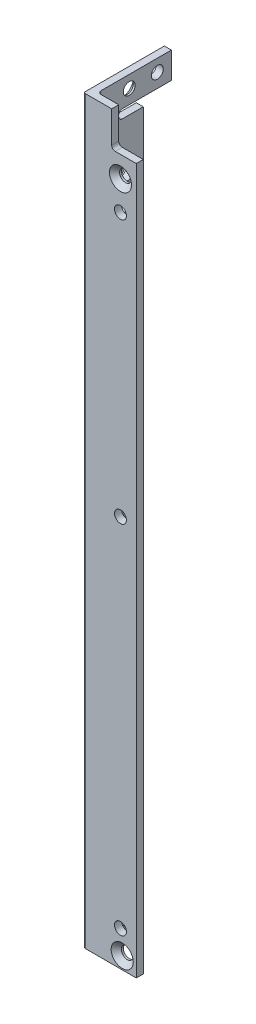
SolidWorks part; units mm, degrees
material "6061-T6 (SS)"
ref_plane "Front Plane" through (0, 0, 0) normal (0, 0, 1) x (1, 0, 0)
ref_plane "Top Plane" through (0, 0, 0) normal (0, 1, 0) x (1, 0, 0)
ref_plane "Right Plane" through (0, 0, 0) normal (1, 0, 0) x (0, 0, -1)
sketch "Sketch1" plane through (0, 0, 0) normal (0, 1, 0) x (1, 0, 0)
  line L1 (0, 0) -> (15, 0)
  line L2 (0, 0) -> (0, 15)
  line L3 (0, 15) -> (15, 15)
  line L4 (15, 0) -> (15, 15)
  line L5 (15, 15) -> (2, 15)
  line L6 (15, 15) -> (15, 2)
  line L7 (15, 2) -> (2, 2)
  line L8 (2, 15) -> (2, 2)
  dimension "D1" = 15
  dimension "D2" = 15
  dimension "D3" = 2
  dimension "D4" = 2
extrude "Boss-Extrude1" add sketch "Sketch1" along normal blind 211 contours L8 L3 L2 L1 L4 L7
sketch "Sketch2" plane through (0, 0, 0) normal (1, 0, 0) x (0, 0, -1)
  line L0 (114.6002, 211) -> (212.4893, 211)
  line L1 (35, 211) -> (50, 211)
  line L2 (0, 211) -> (15, 211) construction
  circle A0 centre (56.7892, 32.4507) radius 1.6
  circle A1 centre (56.7892, 79.8607) radius 1.55
  circle A2 centre (56.7892, 103.4607) radius 1.55
  circle A3 centre (56.7892, 125.1207) radius 1.6
  circle A4 centre (56.7892, 137.8117) radius 1.55
  circle A5 centre (56.7892, 150.8117) radius 1.55
  circle A6 centre (56.7892, 178.5483) radius 1.55
  circle A7 centre (-39.5, 32.4507) radius 1.6
  circle A8 centre (-39.5, 79.8607) radius 1.6
  circle A9 centre (-39.5, 103.4607) radius 1.6
  circle A10 centre (-39.5, 125.1207) radius 1.6
  circle A11 centre (-39.5, 137.8117) radius 1.6
  circle A12 centre (-39.5, 150.8117) radius 1.6
  circle A13 centre (-39.5, 178.5483) radius 1.6
  dimension "D1" = 27.7366
  dimension "D2" = 13
  dimension "D3" = 12.691
  dimension "D4" = 21.66
  dimension "D5" = 23.6
  dimension "D6" = 47.41
  dimension "D7" = 32.4517
sketch "Sketch3" plane through (0, 0, 0) normal (-1, 0, 0) x (0, 0, 1)
  line L0 (-10.5, 211) -> (-10.5, 0)
  line L1 (39.5, 137.8117) -> (-10.5, 137.8117)
  line L3 (39.5, 178.5483) -> (-10.5, 178.5483)
  line L4 (-10.5, 178.5483) -> (39.5, 150.8117)
  line L5 (39.5, 150.8117) -> (-10.5, 150.8117)
  line L6 (-10.5, 150.8117) -> (39.5, 137.8117)
  line L7 (39.5, 125.1207) -> (-10.5, 125.1207)
  line L8 (-10.5, 125.1207) -> (39.5, 103.4607)
  line L9 (39.5, 103.4607) -> (-10.5, 103.4607)
  line L10 (-10.5, 103.4607) -> (39.5, 79.8607)
  line L11 (39.5, 79.8607) -> (-10.5, 79.8607)
  line L12 (-10.5, 79.8607) -> (39.5, 32.4507)
  line L13 (39.5, 32.4507) -> (-10.5, 32.4507)
  line L14 (-15, 211) -> (-15, 0) construction
  dimension "D1" = 4.5
hole_wizard "CSK for M3 Flat Head Machine Screw1" positions "Sketch4" profile "Sketch5" countersink size "M3" standard "ANSI Metric" end condition through all
sketch "Sketch4" plane through (0, 0, 0) normal (-1, 0, 0) x (0, 0, 1)
  line L0 (-6, 87.589) -> (-15, 87.589) construction
  point P0 (-10.5, 178.5483)
  point P3 (-10.5, 150.8117)
  point P6 (-10.5, 125.1207)
  point P9 (-10.5, 91.719)
  point P12 (-10.5, 32.4507)
  point P15 (-10.5, 79.8607)
  point P18 (-10.5, 137.8117)
  dimension "D1" = 4.13
sketch "Sketch5" plane through (0, 178.5483, -10.5) normal (0, 1, 0) x (0, 0, 1)
  line L0 (0, 0) -> (0, 15)
  line L1 (0, 15) -> (1.7, 15)
  line L2 (1.7, 15) -> (1.7, 1.45)
  line L3 (1.7, 1.45) -> (3.15, 0)
  line L5 (3.15, 0) -> (0, 0)
  line L6 (-1.7, 1.45) -> (-3.15, 0) construction
  line L11 (0, -6.35) -> (0, 107.95) construction
  dimension "Thru Hole Dia." = 3.4
  dimension "Thru Hole Depth" = 15
  dimension "Near C'Sink Dia." = 6.3
  dimension "Near C'Sink Angle" = 90
sketch "Sketch6" plane through (0, 0, 0) normal (0, 0, 1) x (1, 0, 0)
  line L0 (15, 211) -> (15, 0) construction
  line L1 (15, 211) -> (8, 211)
  line L2 (15, 211) -> (15, 201)
  line L3 (15, 201) -> (8, 201)
  line L4 (8, 211) -> (8, 201)
  line L5 (0, 211) -> (15, 211) construction
  line L6 (0, 211) -> (0, 0) construction
  dimension "D1" = 0
  dimension "D2" = 8
  dimension "D3" = 10
extrude "Cut-Extrude1" cut sketch "Sketch6" against normal through all
sketch "Sketch7" plane through (0, 0, 0) normal (-1, 0, 0) x (0, 0, 1)
  line L0 (-15, 211) -> (-15, 0) construction
  line L1 (-15, 201) -> (-8, 201)
  line L2 (-15, 201) -> (-15, 203.5)
  line L3 (-15, 203.5) -> (-8, 203.5)
  line L4 (-8, 201) -> (-8, 203.5)
  line L5 (0, 211) -> (0, 0) construction
  dimension "D1" = 8
  dimension "D2" = 2.5
extrude "Cut-Extrude2" cut sketch "Sketch7" against normal through all
sketch "Sketch8" plane through (0, 0, 0) normal (-1, 0, 0) x (0, 0, 1)
  line L0 (0, 211) -> (-15, 211) construction
  line L2 (-15, 211) -> (-15, 203.5) construction
  circle A0 centre (-11, 207.5) radius 1.0458
  dimension "D1" = 3.5
  dimension "D2" = 4
hole_wizard "CSK for M3 Flat Head Machine Screw2" positions "Sketch9" profile "Sketch10" countersink size "M3" standard "ANSI Metric" end condition through all
sketch "Sketch9" plane through (0, 0, 0) normal (-1, 0, 0) x (0, 0, 1)
  point P0 (-11, 207.5)
sketch "Sketch10" plane through (0, 207.5, -11) normal (0, 1, 0) x (0, 0, 1)
  line L0 (0, 0) -> (0, 15)
  line L1 (0, 15) -> (1.7, 15)
  line L2 (1.7, 15) -> (1.7, 1.45)
  line L3 (1.7, 1.45) -> (3.15, 0)
  line L5 (3.15, 0) -> (0, 0)
  line L6 (-1.7, 1.45) -> (-3.15, 0) construction
  line L11 (0, -6.35) -> (0, 107.95) construction
  dimension "Thru Hole Dia." = 3.4
  dimension "Thru Hole Depth" = 15
  dimension "Near C'Sink Dia." = 6.3
  dimension "Near C'Sink Angle" = 90
sketch "Sketch11" plane through (0, 0, 0) normal (0, 0, 1) x (1, 0, 0)
  line L0 (15, 201) -> (15, 0) construction
  line L1 (0, 0) -> (15, 0) construction
  circle A0 centre (11, 3.5) radius 2.9907
  dimension "D1" = 4
  dimension "D2" = 3.5
hole_wizard "CSK for M3 Flat Head Machine Screw3" positions "Sketch14" profile "Sketch15" countersink size "M3" standard "ANSI Metric" end condition through all
sketch "Sketch14" plane through (0, 0, 0) normal (0, 0, 1) x (1, 0, 0)
  line L0 (15, 201) -> (15, 0) construction
  line L1 (0, 211) -> (8, 211) construction
  circle A0 centre (10.5, 195) radius 2.222
  point P0 (11, 3.5)
  point P3 (10.5, 195)
  dimension "D1" = 4.5
  dimension "D2" = 16
sketch "Sketch15" plane through (11, 3.5, 0) normal (1, 0, 0) x (0, -1, 0)
  line L0 (0, 0) -> (0, 15)
  line L1 (0, 15) -> (1.7, 15)
  line L2 (1.7, 15) -> (1.7, 1.45)
  line L3 (1.7, 1.45) -> (3.15, 0)
  line L5 (3.15, 0) -> (0, 0)
  line L6 (-1.7, 1.45) -> (-3.15, 0) construction
  line L11 (0, -6.35) -> (0, 107.95) construction
  dimension "Thru Hole Dia." = 3.4
  dimension "Thru Hole Depth" = 15
  dimension "Near C'Sink Dia." = 6.3
  dimension "Near C'Sink Angle" = 90
fillet "Fillet1" radius 0.5 1 edges at (0, 105.5, 0)
fillet "Fillet2" radius 1 4 edges at (1, 201, -8) (1, 203.5, -8) (2, 105.5, -2) (8, 201, -1)
sketch "Sketch16" plane through (0, 0, 0) normal (-1, 0, 0) x (0, 0, 1)
  line L0 (-0.5, 0) -> (-15, 0) construction
  circle A0 centre (-10.5, 186.68) radius 1.7
  circle A1 centre (-10.5, 111.59) radius 1.7
  circle A2 centre (-10.5, 3) radius 1.7
  circle A3 centre (-10.5, 178.5483) radius 1.7 construction
  circle A4 centre (-10.5, 178.5483) radius 1.7
  point P9 (0, 0)
  point P12 (0, 0)
  dimension "D1" = 186.68
  dimension "D2" = 111.59
  dimension "D3" = 3
extrude "Cut-Extrude3" cut sketch "Sketch16" against normal blind 10
sketch "Sketch17" plane through (0, 0, 0) normal (0, 0, 1) x (1, 0, 0)
  line L0 (0.5, 0) -> (15, 0) construction
  circle A0 centre (10.5, 186.68) radius 1.7
  circle A1 centre (10.5, 111.59) radius 1.7
  circle A2 centre (10.5, 10) radius 1.7
  circle A3 centre (10.5, 195) radius 1.7 construction
  circle A4 centre (10.5, 195) radius 1.7
  dimension "D1" = 10
  dimension "D3" = 186.68
  dimension "D2" = 111.59
extrude "Cut-Extrude4" cut sketch "Sketch17" against normal blind 10
sketch "Sketch20" plane through (0, 0, -15) normal (0, 0, -1) x (-1, 0, 0)
  line L1 (-2, 203.5) -> (0, 203.5)
  line L2 (-2, 203.5) -> (-2, 211)
  line L3 (-2, 211) -> (0, 211)
  line L4 (0, 203.5) -> (0, 211)
  dimension "D1" = 7.5
  dimension "D2" = 2
extrude "Boss-Extrude2" add sketch "Sketch20" along normal blind 8
sketch "Sketch21" plane through (2, 0, 0) normal (1, 0, 0) x (0, 0, -1)
  line L3 (23, 211) -> (23, 203.5) construction
  line L4 (23, 211) -> (3, 211) construction
  circle A0 centre (19, 207.5) radius 1.7
  point P2 (0, 0)
  point P3 (0, 0)
  point P4 (0, 0)
  point P5 (0, 0)
  point P10 (0, 0)
  point P11 (19.0252, 207.2863)
  dimension "D1" = 4
  dimension "D2" = 3.5
extrude "Cut-Extrude5" cut sketch "Sketch21" against normal blind 3 contours A0
